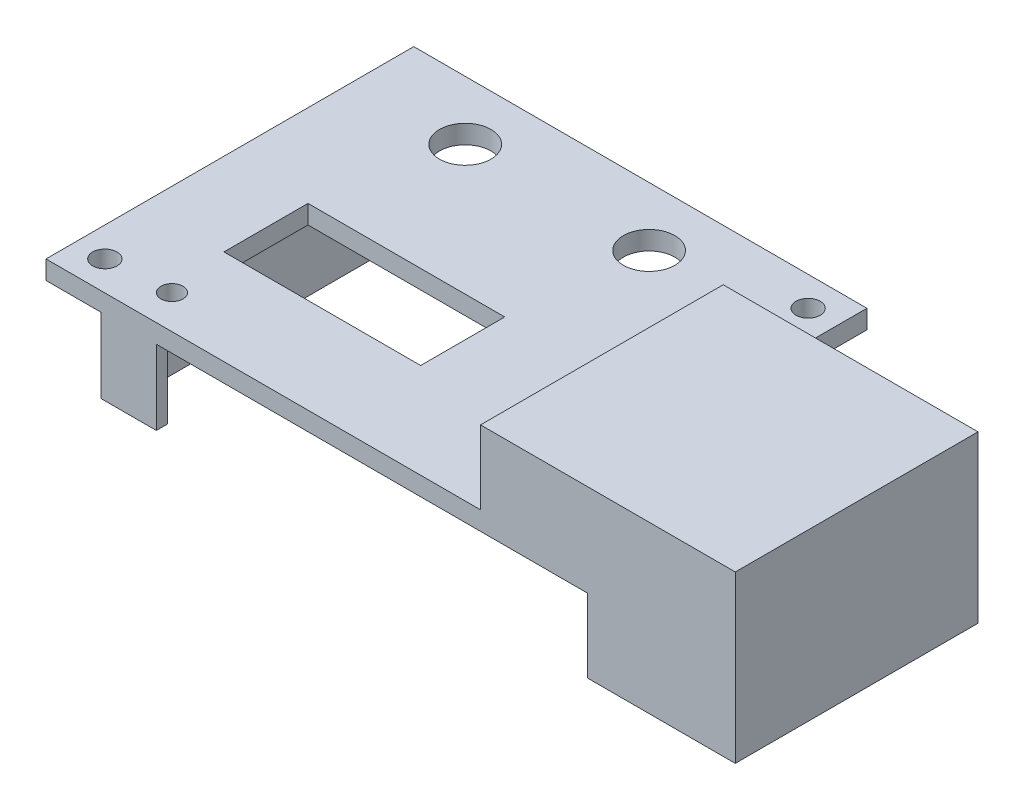
SolidWorks part; units mm, degrees
ref_plane "Front Plane" through (0, 0, 0) normal (0, 0, 1) x (1, 0, 0)
ref_plane "Top Plane" through (0, 0, 0) normal (0, 1, 0) x (1, 0, 0)
ref_plane "Right Plane" through (0, 0, 0) normal (1, 0, 0) x (0, 0, -1)
sketch "Sketch1" plane through (0, 0, 0) normal (0, 1, 0) x (1, 0, 0)
  line L0 (15, 42) -> (40, 42) construction
  line L1 (0, 0) -> (61.618, 0)
  line L2 (0, 0) -> (0, 50)
  line L3 (0, 50) -> (61.618, 50)
  line L4 (61.618, 0) -> (61.618, 50)
  line L5 (11.27, 12.922) -> (41.3182, 12.922)
  line L6 (11.27, 12.922) -> (11.27, 24.352)
  line L7 (11.27, 24.352) -> (41.3182, 24.352)
  line L8 (41.3182, 12.922) -> (41.3182, 24.352)
  line L9 (10, 2) -> (80, 2) construction
  line L10 (10, 2) -> (10, 32) construction
  line L11 (10, 32) -> (80, 32) construction
  line L12 (80, 2) -> (80, 32) construction
  circle A0 centre (15, 42) radius 3.5
  circle A1 centre (40, 42) radius 3.5
  circle A2 centre (12.524, 4.6002) radius 1
  point P19 (12.524, 3.6002)
  point P20 (11.524, 4.6002)
  dimension "D11" = 7
  dimension "D18" = 2
  dimension "D2" = 50
  dimension "D3" = 30.0482
  dimension "D4" = 11.43
  dimension "D5" = 10
  dimension "D6" = 70
  dimension "D7" = 30
  dimension "D8" = 1.27
  dimension "D9" = 10.922
  dimension "D10" = 2
  dimension "D12" = 25
  dimension "D13" = 15
  dimension "D14" = 8
  dimension "D15" = 18.382
  dimension "D16" = 1.524
  dimension "D17" = 1.6002
extrude "Boss-Extrude1" add sketch "Sketch1" along normal blind 2.54
sketch "Sketch3" plane through (0, 0, 0) normal (0, -1, 0) x (1, 0, 0)
  line L1 (10, -2) -> (10, -32) construction
  line L2 (61.618, 0) -> (61.618, -50) construction
  line L3 (10, -2) -> (10, -32)
  line L4 (10, -32) -> (13, -32)
  line L5 (10, -32) -> (80, -32) construction
  line L6 (13, -32) -> (13, -34.54)
  line L7 (13, -34.54) -> (7.46, -34.54)
  line L8 (7.46, -34.54) -> (7.46, 0)
  line L9 (7.46, 0) -> (15, 0)
  line L10 (15, 0) -> (15, -2)
  line L11 (15, -2) -> (10, -2)
  line L13 (10, -32) -> (80, -32) construction
  line L14 (10, -32) -> (10, -34.54)
  line L16 (61.618, -32) -> (60, -32)
  line L17 (61.618, -32) -> (61.618, -34.54)
  line L18 (61.618, -34.54) -> (60, -34.54)
  line L19 (60, -32) -> (60, -34.54)
  line M14 (61.618, 0) -> (0, 0)
  dimension "D1" = 2.54
  dimension "D2" = 2
  dimension "D3" = 2.54
  dimension "D4" = 3
  dimension "D5" = 5
  dimension "D6" = 2.54
extrude "Boss-Extrude2" add sketch "Sketch3" along normal blind 10.16 contours L14 L3 L11 L10 L8 L7 M14
sketch "Sketch4" plane through (0, 0, 0) normal (0, 0, 1) x (1, 0, 0)
  line L0 (59.078, 0) -> (59.078, 12.54)
  line L1 (59.078, 12.54) -> (93.716, 12.54)
  line L2 (93.716, 12.54) -> (93.716, 0)
  line L3 (93.716, 0) -> (91.176, 0)
  line L4 (91.176, 0) -> (91.176, 10)
  line L5 (91.176, 10) -> (61.618, 10)
  line L6 (61.618, 10) -> (61.618, 0)
  line L7 (10, 0) -> (80, 0) construction
  line L8 (61.618, 0) -> (59.078, 0)
  line L9 (10, 0) -> (80, 0) construction
  line L10 (61.618, 2.54) -> (61.618, 0) construction
  dimension "D1" = 2.54
  dimension "D2" = 2.54
  dimension "D3" = 2.54
  dimension "D4" = 11.176
  dimension "D5" = 10
extrude "Boss-Extrude3" add sketch "Sketch4" against normal up to vertex (50 mm away)
sketch "Sketch5" plane through (0, 0, 0) normal (0, 0, 1) x (1, 0, 0)
  line L1 (61.618, 10) -> (91.176, 10)
  line L2 (61.618, 10) -> (61.618, 0)
  line L3 (61.618, 0) -> (91.176, 0)
  line L4 (91.176, 10) -> (91.176, 0)
extrude "Boss-Extrude4" add sketch "Sketch5" against normal up to vertex (2 mm away) up to point (80, 0, -2)
sketch "Sketch6" plane through (0, 0, -32) normal (0, 0, -1) x (-1, 0, 0)
  line L0 (-59.078, 12.54) -> (-59.078, 2.54) construction
  line L5 (-93.716, 12.54) -> (-59.078, 12.54)
  line L6 (-93.716, 12.54) -> (-93.716, 0)
  line L7 (-93.716, 0) -> (-59.078, 0)
  line L8 (-59.078, 12.54) -> (-59.078, 0)
  line L9 (-91.176, 0) -> (-93.716, 0) construction
  line L11 (-91.176, 10) -> (-61.618, 10)
  line L12 (-91.176, 10) -> (-91.176, 2.54)
  line L13 (-91.176, 2.54) -> (-61.618, 2.54)
  line L14 (-61.618, 10) -> (-61.618, 2.54)
extrude "Boss-Extrude5" [suppressed] add sketch "Sketch6" along normal blind 2.54
sketch "Sketch8" [suppressed] plane through (0, 0, -34.54) normal (0, 0, -1) x (-1, 0, 0)
  line L0 (-93.716, 12.54) -> (-93.716, 0) construction
  line L1 (-70, 2.54) -> (-93.716, 2.54)
  line L2 (-70, 2.54) -> (-70, 0)
  line L3 (-70, 0) -> (-93.716, 0)
  line L4 (-93.716, 2.54) -> (-93.716, 0)
  line L5 (-93.716, 0) -> (-75, 0) construction
extrude "Boss-Extrude6" [suppressed] add sketch "Sketch8" along normal up to surface (15.46 mm away)
sketch "Sketch9" plane through (0, -10.16, 0) normal (0, -1, 0) x (1, 0, 0)
  line L8 (10, -34.54) -> (7.46, -34.54) construction
  line L9 (10, -2) -> (17.5615, -2) construction
  line L10 (10, -2) -> (10, -34.54) construction
  line L11 (10, -34.54) -> (17.5615, -34.54) construction
  line L12 (17.5615, -2) -> (17.5615, -34.54) construction
  line L13 (9.5, -1.5) -> (18.0615, -1.5)
  line L14 (18.0615, -1.5) -> (18.0615, -35.04)
  line L15 (9.5, -35.04) -> (18.0615, -35.04)
  line L16 (9.5, -1.5) -> (9.5, -35.04)
  dimension "D1" = 0.5
extrude "Cut-Extrude1" cut sketch "Sketch9" against normal up to surface (10.16 mm away) up to face at (39.8529, 0, -17.22)
sketch "Sketch10" plane through (0, 2.54, 0) normal (0, 1, 0) x (1, 0, 0)
  line L0 (0, 50) -> (61.618, 50) construction
  line L1 (61.618, 0) -> (61.618, 50) construction
  line L2 (0, 50) -> (0, 0) construction
  line L3 (0, 0) -> (59.078, 0) construction
  circle A0 centre (57.618, 46) radius 1.65
  circle A1 centre (4, 4) radius 1.65
  circle A2 centre (12.524, 4.6002) radius 1 construction
  circle A3 centre (12.524, 4.6002) radius 1 construction
  circle A5 centre (12.524, 4.6002) radius 1.5
  dimension "D1" = 3.3
  dimension "D2" = 4
  dimension "D3" = 4
  dimension "D4" = 4
  dimension "D5" = 4
  dimension "D6" = 0.5
extrude "Cut-Extrude2" cut sketch "Sketch10" against normal through all
sketch "Sketch11" plane through (0, 0, 0) normal (0, -1, 0) x (1, 0, 0)
  line L0 (91.176, -32) -> (93.716, -32)
  line L1 (93.716, -32) -> (93.716, 0)
  line L2 (93.716, 0) -> (61.618, 0)
  line L3 (15, 0) -> (93.716, 0) construction
  line L4 (61.618, 0) -> (61.618, -2)
  line L5 (61.618, -2) -> (91.176, -2)
  line L6 (91.176, -2) -> (91.176, -32)
extrude "Boss-Extrude7" add sketch "Sketch11" along normal blind 10
sketch "Sketch12" plane through (0, 0, -32) normal (0, 0, -1) x (-1, 0, 0)
  line L0 (-59.078, 2.54) -> (-61.618, 2.54)
  line L1 (-61.618, 2.54) -> (-61.618, -10)
  line L2 (-61.618, -10) -> (-93.716, -10)
  line L3 (-93.716, -10) -> (-93.716, 12.54)
  line L4 (-93.716, 12.54) -> (-59.078, 12.54)
  line L5 (-59.078, 12.54) -> (-59.078, 2.54)
  circle A0 centre (-85.4356, 4.031) radius 2.794 construction
  circle A1 centre (-85.4356, 4.031) radius 4
  point P14 (-88.2296, 4.031)
  point P15 (-93.716, 4.031)
  point P16 (-84.3574, 12.54)
  point P17 (-85.4356, 4.031)
  dimension "D1" = 5.588
  dimension "D4" = 8
  dimension "D2" = 5.4864
  dimension "D3" = 8.509
extrude "Boss-Extrude8" add sketch "Sketch12" along normal blind 1
sketch "Sketch13" plane through (0, 0, 0) normal (0, 0, 1) x (1, 0, 0)
  line L0 (93.716, -10) -> (61.618, -10) construction
  line L1 (61.618, 0) -> (73.618, 0)
  line L2 (61.618, 0) -> (61.618, -10)
  line L3 (61.618, -10) -> (73.618, -10)
  line L4 (73.618, 0) -> (73.618, -10)
  dimension "D1" = 12
extrude "Cut-Extrude3" cut sketch "Sketch13" against normal blind 10
sketch "Sketch14" plane through (0, 2.54, 0) normal (0, 1, 0) x (1, 0, 0)
  line L0 (11.27, 12.922) -> (41.3182, 12.922) construction
  line L1 (41.3182, 24.352) -> (38.0162, 24.352)
  line L2 (41.3182, 24.352) -> (41.3182, 12.922)
  line L3 (41.3182, 12.922) -> (38.0162, 12.922)
  line L4 (38.0162, 24.352) -> (38.0162, 12.922)
  dimension "D1" = 3.302
extrude "Boss-Extrude9" add sketch "Sketch14" against normal up to surface (2.54 mm away) up to face at (57.618, 0, -47.65)
